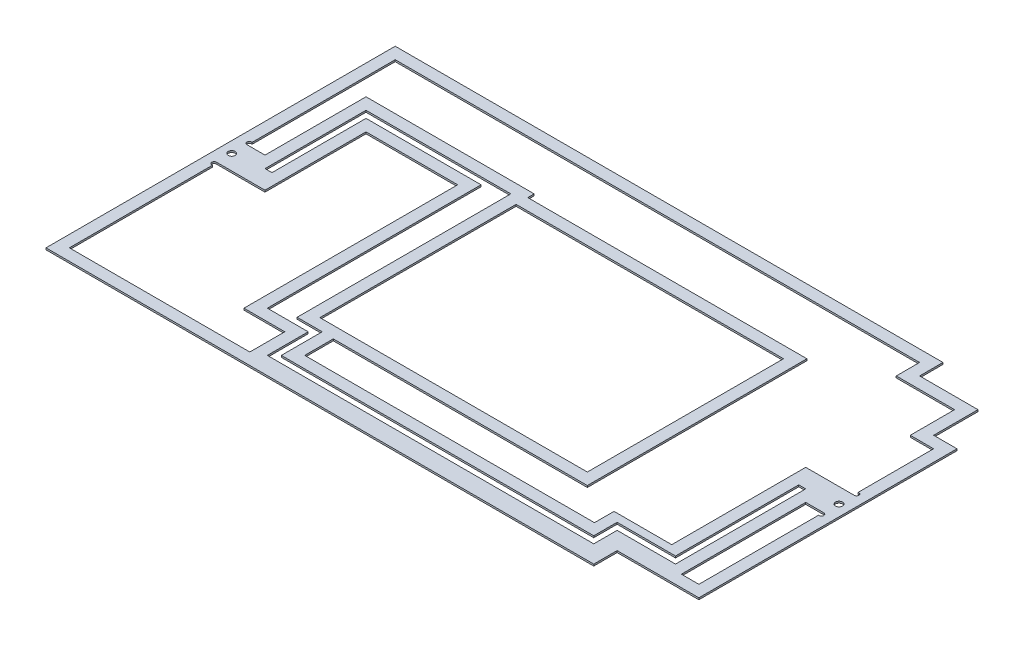
SolidWorks part; units mm, degrees
ref_plane "Front Plane" through (0, 0, 0) normal (0, 0, 1) x (1, 0, 0)
ref_plane "Top Plane" through (0, 0, 0) normal (0, 1, 0) x (1, 0, 0)
ref_plane "Right Plane" through (0, 0, 0) normal (1, 0, 0) x (0, 0, -1)
sketch "Sketch1" plane through (0, 0, 0) normal (0, 1, 0) x (1, 0, 0)
  line L1 (269.5, -149.5) -> (-269.5, -149.5)
  line L2 (269.5, -149.5) -> (269.5, 149.5)
  line L3 (269.5, 149.5) -> (-269.5, 149.5)
  line L4 (-269.5, -149.5) -> (-269.5, 149.5)
  line L5 (269.5, -149.5) -> (-269.5, 149.5) construction
  line L6 (269.5, 149.5) -> (-269.5, -149.5) construction
  point P0 (0, 0)
  dimension "D1" = 299
  dimension "D2" = 539
extrude "Boss-Extrude1" add sketch "Sketch1" against normal blind 1.5
sketch "Sketch10" plane through (0, 0, 0) normal (0, 1, 0) x (1, 0, 0)
  line L0 (269.5, 149.5) -> (199.5, 149.5)
  line L1 (269.5, -149.5) -> (199.5, -149.5)
  line L2 (269.5, -149.5) -> (269.5, -129.5)
  line L3 (269.5, -129.5) -> (199.5, -129.5)
  line L4 (199.5, -149.5) -> (199.5, -129.5)
  line L5 (269.5, 149.5) -> (-269.5, 149.5) construction
  line L6 (199.5, 149.5) -> (199.5, 129.5)
  line L7 (199.5, 129.5) -> (249.5, 129.5)
  line L8 (249.5, 129.5) -> (249.5, 91.5)
  line L9 (249.5, 91.5) -> (269.5, 91.5)
  line L10 (269.5, -149.5) -> (269.5, 149.5) construction
  line L11 (269.5, 91.5) -> (269.5, 149.5)
  dimension "D1" = 70
  dimension "D2" = 20
  dimension "D3" = 20
  dimension "D4" = 70
  dimension "D5" = 20
  dimension "D6" = 58
extrude "Cut-Extrude6" cut sketch "Sketch10" against normal through all
sketch "Sketch2" plane through (0, 0, 0) normal (0, 1, 0) x (1, 0, 0)
  line L0 (-269.5, 0) -> (-260, 0) construction
  line L1 (-269.5, 149.5) -> (-269.5, -149.5) construction
  line L2 (-260, 0) -> (-260, 15) construction
  line L3 (-260, 0) -> (-260, -15) construction
  line L4 (-260, -15) -> (-260, 15) construction
  circle A0 centre (-260, 0) radius 3
  circle A1 centre (-260, 15) radius 2
  circle A2 centre (-260, -15) radius 2
  dimension "D1" = 6
  dimension "D5" = 4
  dimension "D2" = 9.5
  dimension "D3" = 15
  dimension "D4" = 15
extrude "Cut-Extrude1" cut sketch "Sketch2" against normal blind 10
mirror "Mirror1" about plane through (0, 0, 0) normal (1, 0, 0) of "Cut-Extrude1"
sketch "Sketch3" plane through (0, 0, 0) normal (0, 1, 0) x (1, 0, 0)
  line L10 (-228.5, 83.5) -> (-130, 83.5)
  line L11 (-228.5, -3) -> (-228.5, 83.5)
  line L12 (-234.5, 89.5) -> (-234.5, 3)
  line L13 (-110.5, 89.5) -> (-234.5, 89.5)
  line L14 (-110.5, -93.5) -> (-110.5, 89.5)
  line L15 (178.5, -128.5) -> (-89, -128.5)
  line L16 (228.5, 3) -> (228.5, -108.5)
  line L17 (234.5, -114.5) -> (234.5, -3)
  line L18 (-95, -134.5) -> (184.5, -134.5)
  line L19 (-130, 83.5) -> (-130, -99.5)
  line L20 (-228.5, 83.5) -> (-130, 83.5)
  line L21 (-228.5, -3) -> (-228.5, 83.5)
  line L22 (-234.5, 89.5) -> (-234.5, 3)
  line L23 (-110.5, 89.5) -> (-234.5, 89.5)
  line L24 (-110.5, -93.5) -> (-110.5, 89.5)
  line L25 (178.5, -128.5) -> (-89, -128.5)
  line L26 (228.5, 3) -> (228.5, -108.5)
  line L27 (234.5, -114.5) -> (234.5, -3)
  line L28 (-95, -134.5) -> (184.5, -134.5)
  line L29 (-130, 83.5) -> (-130, -99.5)
  line L82 (184.5, -134.5) -> (184.5, -114.5)
  line L83 (184.5, -134.5) -> (184.5, -114.5)
  line L84 (184.5, -114.5) -> (234.5, -114.5)
  line L85 (184.5, -114.5) -> (234.5, -114.5)
  line L86 (228.5, -108.5) -> (178.5, -108.5)
  line L87 (228.5, -108.5) -> (178.5, -108.5)
  line L88 (234.5, -3) -> (260, -3)
  line L89 (234.5, -3) -> (260, -3)
  line L90 (260, 3) -> (228.5, 3)
  line L91 (260, 3) -> (228.5, 3)
  line L92 (-234.5, 3) -> (-260, 3)
  line L93 (-234.5, 3) -> (-260, 3)
  line L94 (-260, -3) -> (-228.5, -3)
  line L95 (-260, -3) -> (-228.5, -3)
  line L96 (178.5, -108.5) -> (178.5, -128.5)
  line L97 (178.5, -108.5) -> (178.5, -128.5)
  line L442 (-130, -99.5) -> (-95, -99.5)
  line L443 (-130, -99.5) -> (-95, -99.5)
  line L444 (-95, -99.5) -> (-95, -134.5)
  line L445 (-95, -99.5) -> (-95, -134.5)
  line L446 (-89, -128.5) -> (-89, -93.5)
  line L447 (-89, -128.5) -> (-89, -93.5)
  line L448 (-89, -93.5) -> (-110.5, -93.5)
  line L449 (-89, -93.5) -> (-110.5, -93.5)
  arc A2 (260, -3) -> (260, 3) centre (260, 0) ccw
  arc A3 (260, -3) -> (260, 3) centre (260, 0) ccw
  arc A16 (-260, 3) -> (-260, -3) centre (-260, 0) ccw
  arc A17 (-260, 3) -> (-260, -3) centre (-260, 0) ccw
  dimension "D1" = 0
sketch "Sketch5" plane through (0, 0, 0) normal (0, 1, 0) x (1, 0, 0)
  line L12 (-100.5, 62.4) -> (-129.5, 62.4)
  line L13 (-129.5, 62.4) -> (-129.5, 15.9)
  line L14 (-129.5, 15.9) -> (-100.5, 15.9)
  line L15 (-100.5, 15.9) -> (-100.5, -15.9)
  line L16 (-100.5, -15.9) -> (-129.5, -15.9)
  line L17 (-129.5, -15.9) -> (-129.5, -62.4)
  line L18 (-129.5, -62.4) -> (-100.5, -62.4)
  line L19 (-100.5, -62.4) -> (-100.5, -84)
  line L20 (-100.5, -84) -> (128.5, -84)
  line L21 (128.5, -84) -> (128.5, 84)
  line L22 (128.5, 84) -> (-100.5, 84)
  line L23 (-100.5, 84) -> (-100.5, 62.4)
  line L31 (-100.5, -62.4) -> (-100.5, -84)
  line L32 (-100.5, -84) -> (128.5, -84)
  line L33 (128.5, -84) -> (128.5, 84)
  line L34 (128.5, 84) -> (-100.5, 84)
  line L35 (-100.5, 84) -> (-100.5, -62.4)
  dimension "D1" = 0
extrude "Cut-Extrude3" cut sketch "Sketch5" against normal through all
sketch "Sketch6" plane through (0, -1.5, 0) normal (0, -1, 0) x (1, 0, 0)
  line L14 (-130, -83.5) -> (-228.5, -83.5)
  line L15 (-228.5, -83.5) -> (-228.5, 3)
  line L16 (-228.5, 3) -> (-260, 3)
  line L17 (-260, -3) -> (-234.5, -3)
  line L18 (-234.5, -3) -> (-234.5, -89.5)
  line L19 (-234.5, -89.5) -> (-110.5, -89.5)
  line L20 (-110.5, -89.5) -> (-110.5, 93.5)
  line L21 (-89, 128.5) -> (178.5, 128.5)
  line L22 (228.5, 108.5) -> (228.5, -3)
  line L23 (228.5, -3) -> (260, -3)
  line L24 (260, 3) -> (234.5, 3)
  line L25 (234.5, 3) -> (234.5, 114.5)
  line L26 (184.5, 134.5) -> (-95, 134.5)
  line L27 (-130, 99.5) -> (-130, -83.5)
  line L28 (-130, -83.5) -> (-228.5, -83.5)
  line L29 (-228.5, -83.5) -> (-228.5, 3)
  line L30 (-228.5, 3) -> (-260, 3)
  line L31 (-260, -3) -> (-234.5, -3)
  line L32 (-234.5, -3) -> (-234.5, -89.5)
  line L33 (-234.5, -89.5) -> (-110.5, -89.5)
  line L34 (-110.5, -89.5) -> (-110.5, 93.5)
  line L35 (-89, 128.5) -> (178.5, 128.5)
  line L36 (228.5, 108.5) -> (228.5, -3)
  line L37 (228.5, -3) -> (260, -3)
  line L38 (260, 3) -> (234.5, 3)
  line L39 (234.5, 3) -> (234.5, 114.5)
  line L40 (184.5, 134.5) -> (-95, 134.5)
  line L41 (-130, 99.5) -> (-130, -83.5)
  line L90 (184.5, 114.5) -> (184.5, 134.5)
  line L91 (184.5, 114.5) -> (184.5, 134.5)
  line L92 (234.5, 114.5) -> (184.5, 114.5)
  line L93 (234.5, 114.5) -> (184.5, 114.5)
  line L94 (178.5, 108.5) -> (228.5, 108.5)
  line L95 (178.5, 108.5) -> (228.5, 108.5)
  line L96 (178.5, 128.5) -> (178.5, 108.5)
  line L97 (178.5, 128.5) -> (178.5, 108.5)
  line L218 (-95, 99.5) -> (-130, 99.5)
  line L219 (-95, 99.5) -> (-130, 99.5)
  line L220 (-95, 134.5) -> (-95, 99.5)
  line L221 (-95, 134.5) -> (-95, 99.5)
  line L222 (-89, 93.5) -> (-89, 128.5)
  line L223 (-89, 93.5) -> (-89, 128.5)
  line L224 (-110.5, 93.5) -> (-89, 93.5)
  line L225 (-110.5, 93.5) -> (-89, 93.5)
  arc A2 (-260, 3) -> (-260, -3) centre (-260, 0) ccw
  arc A3 (260, -3) -> (260, 3) centre (260, 0) ccw
  arc A4 (-260, 3) -> (-260, -3) centre (-260, 0) ccw
  arc A5 (260, -3) -> (260, 3) centre (260, 0) ccw
  dimension "D1" = 0
sketch "Sketch9" plane through (0, 0, 0) normal (0, 1, 0) x (1, 0, 0)
  line L0 (-234.5, 3) -> (-228.5, 3)
  line L1 (234.5, -3) -> (228.5, -3)
  line L14 (-234.5, 3) -> (-260, 3)
  line L15 (-234.5, 89.5) -> (-234.5, 3)
  line L16 (-110.5, 89.5) -> (-234.5, 89.5)
  line L17 (-110.5, -93.5) -> (-110.5, 89.5)
  line L18 (178.5, -128.5) -> (-89, -128.5)
  line L19 (228.5, 3) -> (228.5, -108.5)
  line L20 (260, 3) -> (228.5, 3)
  line L21 (234.5, -3) -> (260, -3)
  line L22 (234.5, -114.5) -> (234.5, -3)
  line L23 (-95, -134.5) -> (184.5, -134.5)
  line L24 (-130, 83.5) -> (-130, -99.5)
  line L25 (-228.5, 83.5) -> (-130, 83.5)
  line L26 (-228.5, -3) -> (-228.5, 83.5)
  line L27 (-260, -3) -> (-228.5, -3)
  line L29 (-234.5, 89.5) -> (-234.5, 3)
  line L30 (-110.5, 89.5) -> (-234.5, 89.5)
  line L31 (-110.5, -93.5) -> (-110.5, 89.5)
  line L32 (178.5, -128.5) -> (-89, -128.5)
  line L33 (228.5, -3) -> (228.5, -108.5)
  line L36 (234.5, -114.5) -> (234.5, -3)
  line L37 (-95, -134.5) -> (184.5, -134.5)
  line L38 (-130, 83.5) -> (-130, -99.5)
  line L39 (-228.5, 83.5) -> (-130, 83.5)
  line L40 (-228.5, 3) -> (-228.5, 83.5)
  line L48 (-89, -93.5) -> (-110.5, -93.5)
  line L49 (-89, -93.5) -> (-110.5, -93.5)
  line L50 (-89, -128.5) -> (-89, -93.5)
  line L51 (-89, -128.5) -> (-89, -93.5)
  line L52 (-95, -99.5) -> (-95, -134.5)
  line L53 (-95, -99.5) -> (-95, -134.5)
  line L54 (-130, -99.5) -> (-95, -99.5)
  line L55 (-130, -99.5) -> (-95, -99.5)
  line L60 (178.5, -108.5) -> (178.5, -128.5)
  line L61 (178.5, -108.5) -> (178.5, -128.5)
  line L62 (228.5, -108.5) -> (178.5, -108.5)
  line L63 (228.5, -108.5) -> (178.5, -108.5)
  line L64 (184.5, -114.5) -> (234.5, -114.5)
  line L65 (184.5, -114.5) -> (234.5, -114.5)
  line L66 (184.5, -134.5) -> (184.5, -114.5)
  line L67 (184.5, -134.5) -> (184.5, -114.5)
  arc A2 (260, -3) -> (260, 3) centre (260, 0) ccw
  arc A3 (-260, 3) -> (-260, -3) centre (-260, 0) ccw
  dimension "D1" = 0
extrude "Cut-Extrude5" cut sketch "Sketch9" against normal through all
sketch "Sketch7" plane through (0, 0, 0) normal (0, 1, 0) x (1, 0, 0)
  line L0 (-259.5, -13) -> (-218.5, -13)
  line L5 (-259.5, 139.5) -> (-244.5, 139.5)
  line L6 (-259.5, 139.5) -> (-259.5, 13)
  line L7 (-259.5, 13) -> (-244.5, 13)
  line L8 (-244.5, 99.5) -> (-244.5, 13)
  line L9 (-218.5, -13) -> (-218.5, 73.5)
  line L10 (-218.5, 73.5) -> (-140, 73.5)
  line L11 (-140, 73.5) -> (-140, -109.5)
  line L12 (-140, -139.5) -> (-259.5, -139.5)
  line L13 (-259.5, -139.5) -> (-259.5, -13)
  line L14 (-100.5, 99.5) -> (-100.5, 94)
  line L15 (-100.5, 94) -> (138.5, 94)
  line L16 (138.5, 94) -> (138.5, -94)
  line L17 (138.5, -94) -> (-79, -94)
  line L18 (-79, -94) -> (-79, -118.5)
  line L19 (-79, -118.5) -> (169.1078, -118.5)
  line L20 (218.5, -101.7287) -> (218.5, 13)
  line L21 (218.5, 13) -> (259.5, 13)
  line L22 (259.5, 13) -> (259.5, 81.5)
  line L23 (189.5, 139.5) -> (-100.5, 139.5)
  line L24 (-269.5, 149.5) -> (-269.5, -149.5) construction
  line L25 (199.5, 149.5) -> (-269.5, 149.5) construction
  line L26 (-234.5, 3) -> (-234.5, 89.5) construction
  line L27 (-260, 3) -> (-234.5, 3) construction
  line L28 (-228.5, 83.5) -> (-228.5, -3) construction
  line L29 (-130, 83.5) -> (-228.5, 83.5) construction
  line L30 (-130, -99.5) -> (-130, 83.5) construction
  line L31 (-269.5, -149.5) -> (199.5, -149.5) construction
  line L32 (-228.5, -3) -> (-260, -3) construction
  line L33 (128.5, 84) -> (-100.5, 84) construction
  line L34 (-110.5, 89.5) -> (-110.5, -93.5) construction
  line L35 (269.5, -129.5) -> (269.5, 91.5) construction
  line L37 (228.5, -108.5) -> (228.5, 3) construction
  line L38 (-89, -128.5) -> (178.5, -128.5) construction
  line L39 (-100.5, -84) -> (128.5, -84) construction
  line L40 (128.5, -84) -> (128.5, 84) construction
  line L42 (244.5, -13) -> (259.5, -13)
  line L43 (244.5, -13) -> (244.5, -119.5)
  line L44 (244.5, -119.5) -> (259.5, -119.5)
  line L45 (259.5, -13) -> (259.5, -119.5)
  line L46 (234.5, -3) -> (234.5, -114.5) construction
  line L47 (189.5, 139.5) -> (189.5, 119.5)
  line L48 (-140, -139.5) -> (-105, -139.5)
  line L49 (-105, -139.5) -> (-105, -109.5)
  line L50 (-105, -109.5) -> (-140, -109.5)
  line L51 (-244.5, 139.5) -> (-100.5, 139.5)
  line L52 (-244.5, 99.5) -> (-100.5, 99.5)
  line L53 (-110.5, 89.5) -> (-234.5, 89.5) construction
  line L54 (-130, -99.5) -> (-95, -99.5) construction
  line L55 (-95, -99.5) -> (-95, -134.5) construction
  line L56 (-89, -128.5) -> (-89, -93.5) construction
  line L57 (189.5, 119.5) -> (239.5, 119.5)
  line L58 (239.5, 119.5) -> (239.5, 81.5)
  line L59 (239.5, 81.5) -> (259.5, 81.5)
  line L60 (169.1078, -118.5) -> (169.1078, -101.7287)
  line L61 (169.1078, -101.7287) -> (218.5, -101.7287)
  line L62 (269.5, -129.5) -> (199.5, -129.5) construction
  line L63 (199.5, 149.5) -> (199.5, 129.5) construction
  line L64 (199.5, 129.5) -> (249.5, 129.5) construction
  line L65 (249.5, 129.5) -> (249.5, 91.5) construction
  line L66 (249.5, 91.5) -> (269.5, 91.5) construction
  circle A0 centre (260, 0) radius 3 construction
  point P92 (259.5, 91.5)
  dimension "D1" = 10
  dimension "D2" = 10
  dimension "D3" = 10
  dimension "D4" = 10
  dimension "D5" = 10
  dimension "D6" = 10
  dimension "D7" = 10
  dimension "D8" = 10
  dimension "D9" = 10
  dimension "D10" = 10
  dimension "D11" = 10
  dimension "D12" = 10
  dimension "D13" = 10
  dimension "D14" = 10
  dimension "D16" = 10
  dimension "D17" = 10
  dimension "D19" = 10
  dimension "D20" = 10
  dimension "D22" = 10
  dimension "D23" = 10
  dimension "D25" = 10
  dimension "D26" = 10
  dimension "D27" = 10
  dimension "D18" = 10
  dimension "D24" = 10
  dimension "D28" = 10
  dimension "D29" = 10
  dimension "D30" = 10
  dimension "D31" = 10
  dimension "D15" = 10
  dimension "D21" = 10
extrude "Cut-Extrude4" cut sketch "Sketch7" against normal through all
equation "\"D2@Sketch7\"=\"D1@Sketch7\""
equation "\"D3@Sketch7\"=\"D1@Sketch7\""
equation "\"D4@Sketch7\"=\"D1@Sketch7\""
equation "\"D5@Sketch7\"=\"D1@Sketch7\""
equation "\"D6@Sketch7\"=\"D1@Sketch7\""
equation "\"D7@Sketch7\"=\"D1@Sketch7\""
equation "\"D8@Sketch7\"=\"D1@Sketch7\""
equation "\"D9@Sketch7\"=\"D1@Sketch7\""
equation "\"D10@Sketch7\"=\"D1@Sketch7\""
equation "\"D11@Sketch7\"=\"D1@Sketch7\""
equation "\"D12@Sketch7\"=\"D1@Sketch7\""
equation "\"D13@Sketch7\"=\"D1@Sketch7\""
equation "\"D14@Sketch7\"=\"D1@Sketch7\""
equation "\"D16@Sketch7\"=\"D1@Sketch7\""
equation "\"D17@Sketch7\"=\"D1@Sketch7\""
equation "\"D19@Sketch7\"=\"D1@Sketch7\""
equation "\"D20@Sketch7\"=\"D1@Sketch7\""
equation "\"D22@Sketch7\"=\"D1@Sketch7\""
equation "\"D23@Sketch7\"=\"D1@Sketch7\""
equation "\"D25@Sketch7\"=\"D1@Sketch7\""
equation "\"D18@Sketch7\"=\"D1@Sketch7\""
equation "\"D24@Sketch7\"=\"D1@Sketch7\""
equation "\"D28@Sketch7\"=\"D1@Sketch7\""
equation "\"D29@Sketch7\"=\"D1@Sketch7\""
equation "\"D30@Sketch7\"=\"D1@Sketch7\""
equation "\"D31@Sketch7\"=\"D1@Sketch7\""
